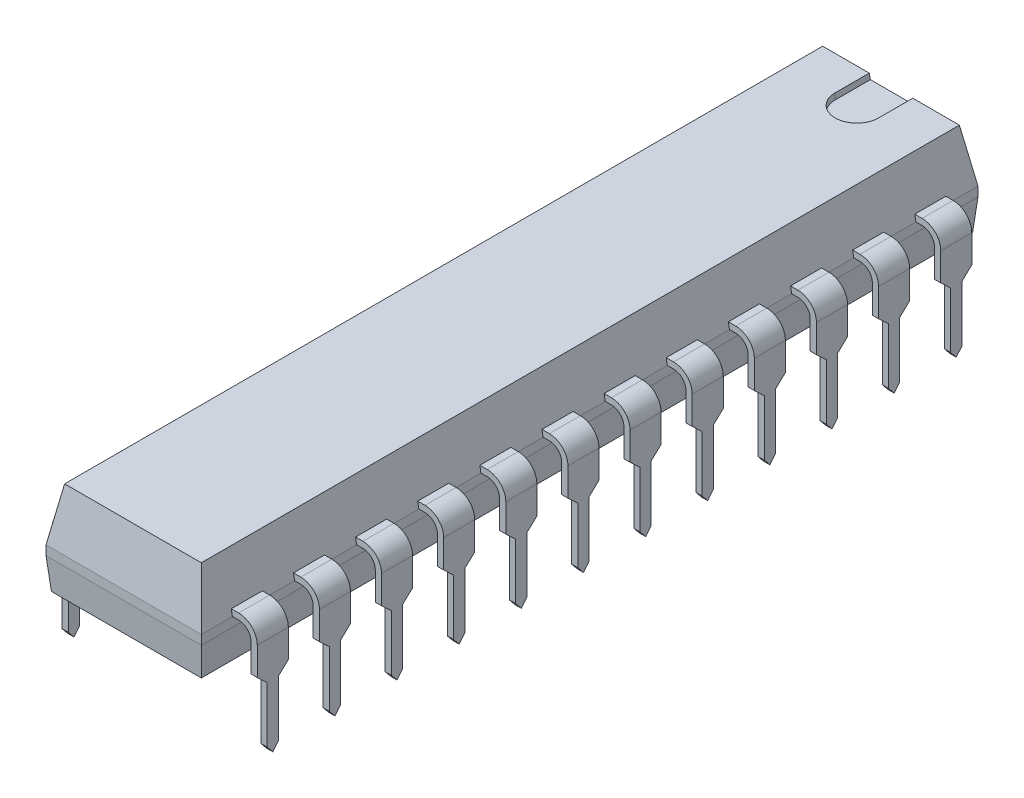
SolidWorks part; units mm, degrees
ref_plane "Plane1" through (0, 0, 0) normal (0, 0, 1) x (1, 0, 0)
ref_plane "Plane2" through (0, 0, 0) normal (0, 1, 0) x (1, 0, 0)
ref_plane "Plane3" through (0, 0, 0) normal (1, 0, 0) x (0, 0, -1)
ref_plane "Plane4" through (0, 0.381, 0) normal (0, 1, 0) x (-1, 0, 0)
sketch "Sketch2" plane through (0, 0.381, 0) normal (0, 1, 0) x (0, 0, 1)
  line L1 (-1.905, 7.112) -> (29.845, 7.112)
  line L2 (-1.905, 7.112) -> (-1.905, 0.762)
  line L3 (-1.905, 0.762) -> (29.845, 0.762)
  line L4 (29.845, 7.112) -> (29.845, 0.762)
  dimension "D1" = 6.35
  dimension "D2" = 31.75
  dimension "D3" = 1.905
  dimension "D4" = 0.762
extrude "Base-Extrude" add sketch "Sketch2" along normal blind 3.81
chamfer "Chamfer1" distance 2.159 angle 10 4 edges at (3.937, 4.191, 29.845) (7.112, 4.191, 13.97) (3.937, 4.191, -1.905) (0.762, 4.191, 13.97)
chamfer "Chamfer2" distance 1.27 angle 5 4 edges at (7.112, 0.381, 13.97) (3.937, 0.381, 29.845) (0.762, 0.381, 13.97) (3.937, 0.381, -1.905)
sketch "Sketch3" plane through (0, 4.191, 0) normal (0, 1, 0) x (-1, 0, 0)
  line L0 (-0.762, -1.905) -> (-7.112, -1.905) construction
  line L1 (-3.048, -1.905) -> (-4.826, -1.905)
  line L2 (-3.937, -1.905) -> (-3.937, 1.8103) construction
  line L3 (-3.048, -1.905) -> (-3.048, -0.127)
  line L4 (-0.762, 29.845) -> (-0.762, -1.905) construction
  line L5 (-4.826, -1.905) -> (-4.826, -0.127)
  arc A0 (-3.048, -0.127) -> (-4.826, -0.127) centre (-3.937, -0.127) ccw
  dimension "D2" = 0.889
  dimension "D1" = 1.778
  dimension "D3" = 1.778
  dimension "D4" = 3.175
extrude "Cut-Extrude1" cut sketch "Sketch3" against normal blind 0.254
sketch "Sketch4" plane through (0, 0, 0) normal (0, 0, -1) x (-1, 0, 0)
  line L0 (-1.1903, 2.032) -> (-0.508, 2.032)
  line L1 (-0.762, 2.032) -> (-7.112, 2.032) construction
  line L2 (0, 1.524) -> (0, -2.5654)
  arc A0 (-0.508, 2.032) -> (0, 1.524) centre (-0.508, 1.524) cw
  dimension "D1" = 0.508
  dimension "D2" = 2.5654
extrude "Boss-Extrude-Thin1" add sketch "Sketch4" along normal mid plane 1.27 thin thin type one direction reverse wall 0.254
sketch "Sketch5" plane through (0, 0, 0) normal (1, 0, 0) x (0, 0, -1)
  line L0 (0.635, -2.5654) -> (-0.635, -2.5654) construction
  line L1 (-0.635, 1.524) -> (-0.635, -2.5654) construction
  line L2 (0, -2.5654) -> (-0.635, -2.5654)
  line L3 (-0.635, 0.381) -> (-0.635, -2.5654)
  line L4 (-0.635, 0.381) -> (-0.2286, 0)
  line L5 (-0.2286, 0) -> (-0.2286, -2.286)
  line L6 (-0.2286, -2.286) -> (0, -2.5654)
  line L7 (50, 0.381) -> (-50, 0.381) construction
  dimension "D1" = 0.2286
  dimension "D2" = 2.286
extrude "Cut-Extrude2" cut sketch "Sketch5" against normal through all
mirror "Mirror1" about plane through (0, 0, 0) normal (0, 0, 1) of "Cut-Extrude2"
ref_plane "Plane5" through (3.937, 0, 0) normal (-1, 0, 0) x (0, 0, 1)
pattern_linear "LPattern1" count 12 spacing 2.54 along (0, 0, 1) of "Cut-Extrude2", "Mirror1", "Boss-Extrude-Thin1"
mirror "Mirror2" about plane through (3.937, 0, 0) normal (-1, 0, 0) of "LPattern1", "Boss-Extrude-Thin1", "Cut-Extrude2", "Mirror1"
sketch "Component_Outline" plane through (0, 0, 0) normal (0, 1, 0) x (1, 0, 0)
  line L0 (0.762, -29.845) -> (0.762, -28.575)
  line L1 (0.762, -28.575) -> (-0.254, -28.575)
  line L2 (-0.254, -28.575) -> (-0.254, -27.305)
  line L3 (-0.254, -27.305) -> (0.762, -27.305)
  line L4 (0.762, -27.305) -> (0.762, -26.035)
  line L5 (0.762, -26.035) -> (-0.254, -26.035)
  line L6 (-0.254, -26.035) -> (-0.254, -24.765)
  line L7 (-0.254, -24.765) -> (0.762, -24.765)
  line L8 (0.762, -24.765) -> (0.762, -23.495)
  line L9 (0.762, -23.495) -> (-0.254, -23.495)
  line L10 (-0.254, -23.495) -> (-0.254, -22.225)
  line L11 (-0.254, -22.225) -> (0.762, -22.225)
  line L12 (0.762, -22.225) -> (0.762, -20.955)
  line L13 (0.762, -20.955) -> (-0.254, -20.955)
  line L14 (-0.254, -20.955) -> (-0.254, -19.685)
  line L15 (-0.254, -19.685) -> (0.762, -19.685)
  line L16 (0.762, -19.685) -> (0.762, -18.415)
  line L17 (0.762, -18.415) -> (-0.254, -18.415)
  line L18 (-0.254, -18.415) -> (-0.254, -17.145)
  line L19 (-0.254, -17.145) -> (0.762, -17.145)
  line L20 (0.762, -17.145) -> (0.762, -15.875)
  line L21 (0.762, -15.875) -> (-0.254, -15.875)
  line L22 (-0.254, -15.875) -> (-0.254, -14.605)
  line L23 (-0.254, -14.605) -> (0.762, -14.605)
  line L24 (0.762, -14.605) -> (0.762, -13.335)
  line L25 (0.762, -13.335) -> (-0.254, -13.335)
  line L26 (-0.254, -13.335) -> (-0.254, -12.065)
  line L27 (-0.254, -12.065) -> (0.762, -12.065)
  line L28 (0.762, -12.065) -> (0.762, -10.795)
  line L29 (0.762, -10.795) -> (-0.254, -10.795)
  line L30 (-0.254, -10.795) -> (-0.254, -9.525)
  line L31 (-0.254, -9.525) -> (0.762, -9.525)
  line L32 (0.762, -9.525) -> (0.762, -8.255)
  line L33 (0.762, -8.255) -> (-0.254, -8.255)
  line L34 (-0.254, -8.255) -> (-0.254, -6.985)
  line L35 (-0.254, -6.985) -> (0.762, -6.985)
  line L36 (0.762, -6.985) -> (0.762, -5.715)
  line L37 (0.762, -5.715) -> (-0.254, -5.715)
  line L38 (-0.254, -5.715) -> (-0.254, -4.445)
  line L39 (-0.254, -4.445) -> (0.762, -4.445)
  line L40 (0.762, -4.445) -> (0.762, -3.175)
  line L41 (0.762, -3.175) -> (-0.254, -3.175)
  line L42 (-0.254, -3.175) -> (-0.254, -1.905)
  line L43 (-0.254, -1.905) -> (0.762, -1.905)
  line L44 (0.762, -1.905) -> (0.762, -0.635)
  line L45 (0.762, -0.635) -> (-0.254, -0.635)
  line L46 (-0.254, -0.635) -> (-0.254, 0.635)
  line L47 (-0.254, 0.635) -> (0.762, 0.635)
  line L48 (0.762, 0.635) -> (0.762, 1.905)
  line L49 (3.937, -29.7339) -> (3.937, 1.905) construction
  line L50 (7.0009, -29.7339) -> (0.8731, -29.7339) construction
  line L51 (7.112, 1.905) -> (0.762, 1.905) construction
  line L52 (7.112, 0.635) -> (7.112, 1.905)
  line L53 (8.128, 0.635) -> (7.112, 0.635)
  line L54 (8.128, -0.635) -> (8.128, 0.635)
  line L55 (7.112, -0.635) -> (8.128, -0.635)
  line L56 (7.112, -1.905) -> (7.112, -0.635)
  line L57 (8.128, -1.905) -> (7.112, -1.905)
  line L58 (8.128, -3.175) -> (8.128, -1.905)
  line L59 (7.112, -3.175) -> (8.128, -3.175)
  line L60 (7.112, -4.445) -> (7.112, -3.175)
  line L61 (8.128, -4.445) -> (7.112, -4.445)
  line L62 (8.128, -5.715) -> (8.128, -4.445)
  line L63 (7.112, -5.715) -> (8.128, -5.715)
  line L64 (7.112, -6.985) -> (7.112, -5.715)
  line L65 (8.128, -6.985) -> (7.112, -6.985)
  line L66 (8.128, -8.255) -> (8.128, -6.985)
  line L67 (7.112, -8.255) -> (8.128, -8.255)
  line L68 (7.112, -9.525) -> (7.112, -8.255)
  line L69 (8.128, -9.525) -> (7.112, -9.525)
  line L70 (8.128, -10.795) -> (8.128, -9.525)
  line L71 (7.112, -10.795) -> (8.128, -10.795)
  line L72 (7.112, -12.065) -> (7.112, -10.795)
  line L73 (8.128, -12.065) -> (7.112, -12.065)
  line L74 (8.128, -13.335) -> (8.128, -12.065)
  line L75 (7.112, -13.335) -> (8.128, -13.335)
  line L76 (7.112, -14.605) -> (7.112, -13.335)
  line L77 (8.128, -14.605) -> (7.112, -14.605)
  line L78 (8.128, -15.875) -> (8.128, -14.605)
  line L79 (7.112, -15.875) -> (8.128, -15.875)
  line L80 (7.112, -17.145) -> (7.112, -15.875)
  line L81 (8.128, -17.145) -> (7.112, -17.145)
  line L82 (8.128, -18.415) -> (8.128, -17.145)
  line L83 (7.112, -18.415) -> (8.128, -18.415)
  line L84 (7.112, -19.685) -> (7.112, -18.415)
  line L85 (8.128, -19.685) -> (7.112, -19.685)
  line L86 (8.128, -20.955) -> (8.128, -19.685)
  line L87 (7.112, -20.955) -> (8.128, -20.955)
  line L88 (7.112, -22.225) -> (7.112, -20.955)
  line L89 (8.128, -22.225) -> (7.112, -22.225)
  line L90 (8.128, -23.495) -> (8.128, -22.225)
  line L91 (7.112, -23.495) -> (8.128, -23.495)
  line L92 (7.112, -24.765) -> (7.112, -23.495)
  line L93 (8.128, -24.765) -> (7.112, -24.765)
  line L94 (8.128, -26.035) -> (8.128, -24.765)
  line L95 (7.112, -26.035) -> (8.128, -26.035)
  line L96 (7.112, -27.305) -> (7.112, -26.035)
  line L97 (8.128, -27.305) -> (7.112, -27.305)
  line L98 (8.128, -28.575) -> (8.128, -27.305)
  line L99 (7.112, -28.575) -> (8.128, -28.575)
  line L100 (7.112, -29.845) -> (7.112, -28.575)
  line L101 (0.762, -29.845) -> (7.112, -29.845)
  line L102 (0.762, 1.905) -> (7.112, 1.905)
